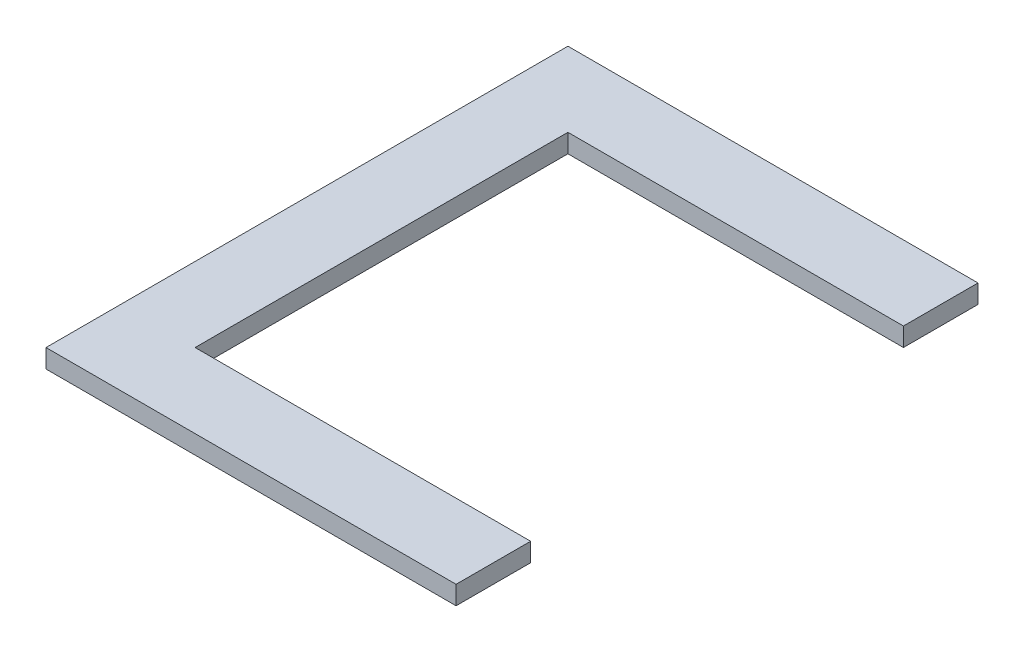
SolidWorks part; units mm, degrees
material "5052-H32"
ref_plane "Front Plane" through (0, 0, 0) normal (0, 0, 1) x (1, 0, 0)
ref_plane "Top Plane" through (0, 0, 0) normal (0, 1, 0) x (1, 0, 0)
ref_plane "Right Plane" through (0, 0, 0) normal (1, 0, 0) x (0, 0, -1)
sketch "Sketch1" plane through (0, 0, 0) normal (0, 1, 0) x (1, 0, 0)
  line L0 (-89.9925, 0) -> (89.9925, 0) construction
  line L1 (0, -84.8032) -> (0, 84.8032) construction
  line L2 (0, -38.1) -> (0, 38.1) construction
  line L3 (0, 38.1) -> (63.5, 38.1) construction
  line L4 (0, -38.1) -> (63.5, -38.1) construction
  line L5 (63.5, 31.75) -> (63.5, 44.45)
  line L6 (63.5, -44.45) -> (63.5, -31.75)
  line L7 (63.5, 44.45) -> (-6.35, 44.45)
  line L8 (-6.35, 44.45) -> (-6.35, -44.45)
  line L9 (-6.35, -44.45) -> (63.5, -44.45)
  line L10 (63.5, 31.75) -> (6.35, 31.75)
  line L11 (6.35, 31.75) -> (6.35, -31.75)
  line L12 (6.35, -31.75) -> (63.5, -31.75)
  point P4 (0, 0)
  point P8 (0, 0)
  point P11 (0, 0)
  point P16 (63.5, 38.1)
  point P20 (63.5, -38.1)
  dimension "D1" = 76.2
  dimension "D2" = 63.5
  dimension "D3" = 12.7
  dimension "D4" = 12.7
  dimension "D5" = 69.85
  dimension "D6" = 57.15
extrude "Boss-Extrude1" add sketch "Sketch1" along normal blind 3.175
